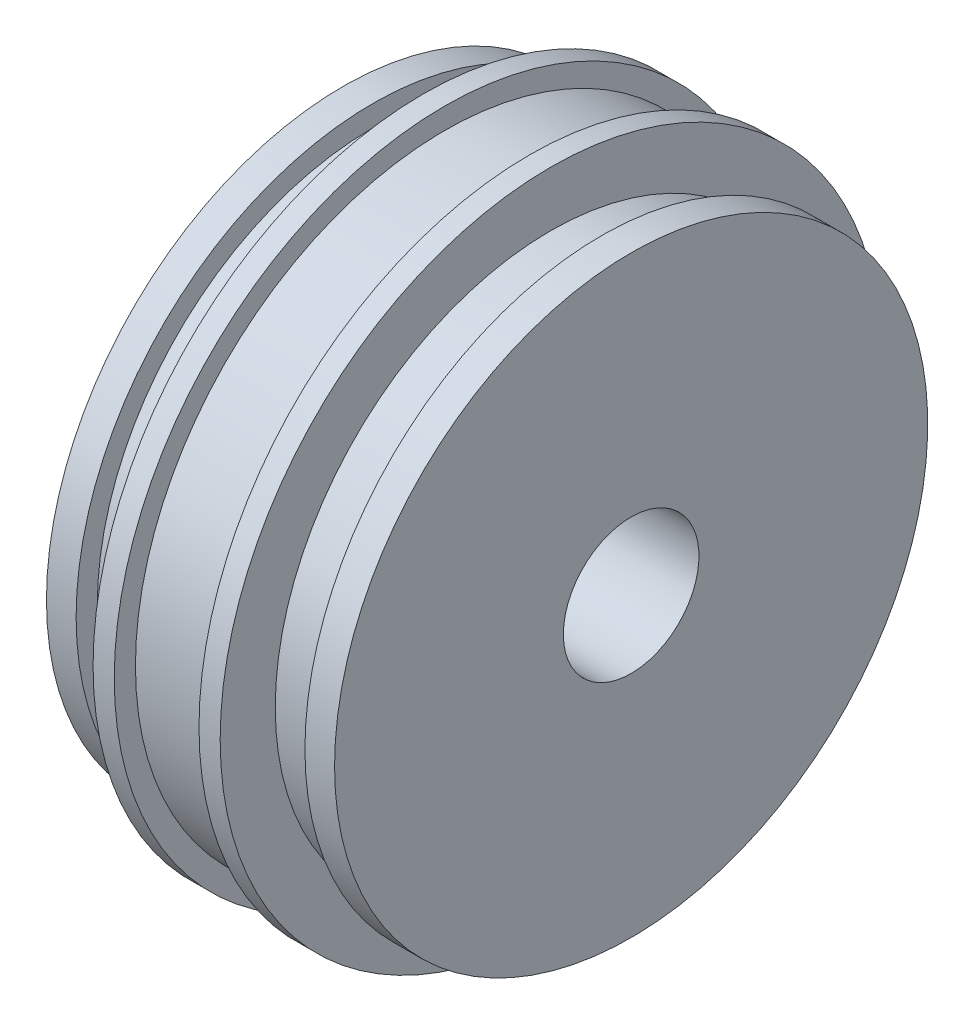
SolidWorks part; units mm, degrees
ref_plane "Alzado" through (0, 0, 0) normal (0, 0, 1) x (1, 0, 0)
ref_plane "Planta" through (0, 0, 0) normal (0, 1, 0) x (1, 0, 0)
ref_plane "Vista lateral" through (0, 0, 0) normal (1, 0, 0) x (0, 0, -1)
sketch "Croquis1" plane through (0, 0, 0) normal (0, 0, 1) x (1, 0, 0)
  line L0 (7.3461, 8.5) -> (7.3461, 35.5)
  line L1 (7.3461, 35.5) -> (10.8461, 35.5)
  line L2 (10.8461, 35.5) -> (10.8461, 33)
  line L3 (10.8461, 33) -> (16.8461, 33)
  line L4 (41.3461, 8.5) -> (41.3461, 35.5)
  line L5 (16.8461, 33) -> (16.8461, 39.5)
  line L6 (16.8461, 39.5) -> (19.3461, 39.5)
  line L7 (19.3461, 39.5) -> (19.3461, 37)
  line L8 (19.3461, 37) -> (29.3461, 37)
  line L9 (29.3461, 37) -> (29.3461, 39.5)
  line L10 (29.3461, 39.5) -> (31.8461, 39.5)
  line L11 (31.8461, 39.5) -> (31.8461, 33)
  line L12 (31.8461, 33) -> (37.8461, 33)
  line L13 (37.8461, 33) -> (37.8461, 35.5)
  line L14 (37.8461, 35.5) -> (41.3461, 35.5)
  line L16 (7.3461, 8.5) -> (41.3461, 8.5)
  line L17 (-1, 0.5) -> (59.7246, 0.5) construction
  point P0 (34.8461, 33)
  dimension "D1" = 34
  dimension "D2" = 3.5
  dimension "D3" = 3.5
  dimension "D4" = 6
  dimension "D5" = 6
  dimension "D6" = 2.5
  dimension "D7" = 2.5
  dimension "D8" = 78
  dimension "D9" = 16
  dimension "D10" = 78
  dimension "D11" = 70
  dimension "D12" = 70
  dimension "D13" = 65
  dimension "D14" = 65
  dimension "D15" = 73
revolve "Revolución1" add sketch "Croquis1" angle 360 about L17
